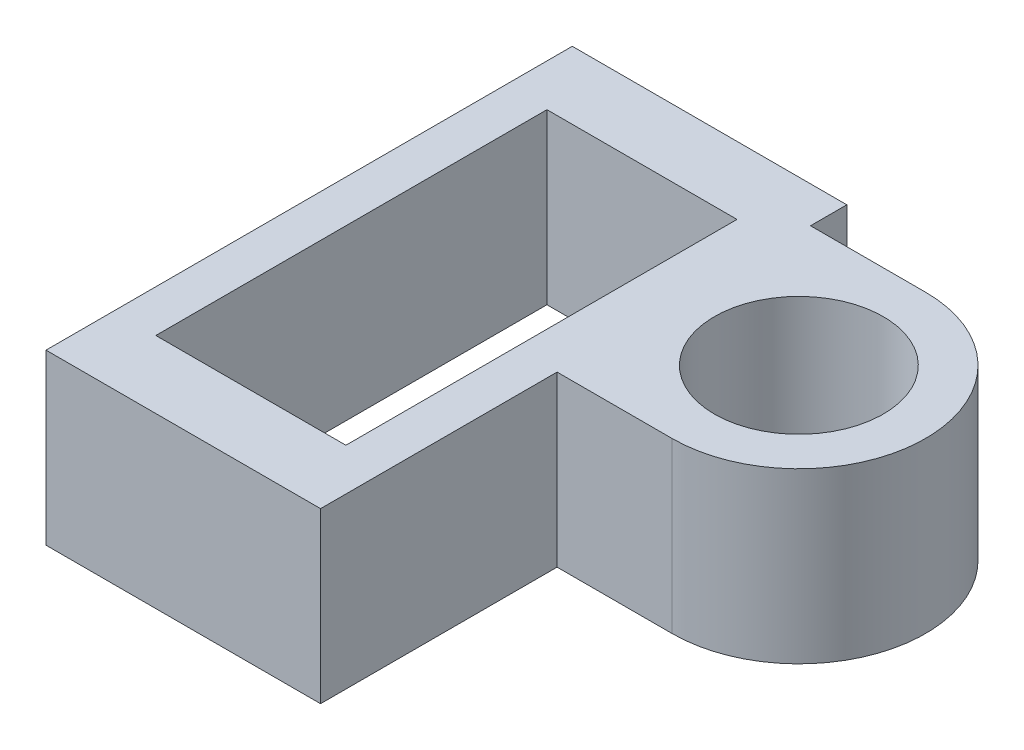
SolidWorks part; units mm, degrees
ref_plane "Front Plane" through (0, 0, 0) normal (0, 0, 1) x (1, 0, 0)
ref_plane "Top Plane" through (0, 0, 0) normal (0, 1, 0) x (1, 0, 0)
ref_plane "Right Plane" through (0, 0, 0) normal (1, 0, 0) x (0, 0, -1)
sketch "Sketch1" plane through (0, 0, 0) normal (0, 1, 0) x (1, 0, 0)
  line L0 (-61.4299, 68.961) -> (-61.4299, 54.61) construction
  line L1 (0, 0) -> (-82.0674, 0)
  line L2 (0, 0) -> (0, 79.121)
  line L3 (0, 79.121) -> (-82.0674, 79.121)
  line L4 (-82.0674, 0) -> (-82.0674, 79.121)
  line L5 (-75.7174, 68.961) -> (-47.1424, 68.961)
  line L6 (-75.7174, 68.961) -> (-75.7174, 10.16)
  line L7 (-75.7174, 10.16) -> (-47.1424, 10.16)
  line L8 (-47.1424, 68.961) -> (-47.1424, 10.16)
  circle A0 centre (-61.4299, 54.61) radius 5.5245 construction
  circle A1 centre (-23.495, 54.61) radius 12.7
  circle A2 centre (-23.495, 54.61) radius 34.0614 construction
  circle A3 centre (-23.495, 54.61) radius 33.2359 construction
  circle A4 centre (-61.4299, 54.61) radius 4.699 construction
  dimension "D6" = 11.049
  dimension "D7" = 25.4
  dimension "D10" = 68.1228
  dimension "D9" = 0.8255
  dimension "D11" = 0.8255
  dimension "D1" = 58.801
  dimension "D2" = 28.575
  dimension "D3" = 10.16
  dimension "D4" = 14.351
  dimension "D5" = 6.35
  dimension "D8" = 23.495
  dimension "D12" = 10.16
extrude "Boss-Extrude1" add sketch "Sketch1" along normal blind 25.4
sketch "Sketch2" plane through (0, 25.4, 0) normal (0, 1, 0) x (1, 0, 0)
  line L0 (-40.7924, 0) -> (-40.7924, 35.56)
  line L1 (-82.0674, 0) -> (0, 0) construction
  line L2 (-40.7924, 35.56) -> (-23.495, 35.56)
  line L3 (-40.7924, 79.121) -> (-40.7924, 73.66)
  line L4 (0, 79.121) -> (-82.0674, 79.121) construction
  line L5 (-40.7924, 73.66) -> (-23.495, 73.66)
  line L6 (-47.1424, 68.961) -> (-47.1424, 76.581) construction
  line L7 (-40.7924, 0) -> (0, 0)
  line L8 (0, 0) -> (0, 79.121)
  line L9 (0, 79.121) -> (-40.7924, 79.121)
  arc A0 (-23.495, 73.66) -> (-23.495, 35.56) centre (-23.495, 54.61) cw
  circle A1 centre (-23.495, 54.61) radius 12.7 construction
  dimension "D1" = 6.35
  dimension "D2" = 6.35
extrude "Cut-Extrude1" cut sketch "Sketch2" against normal up to next
